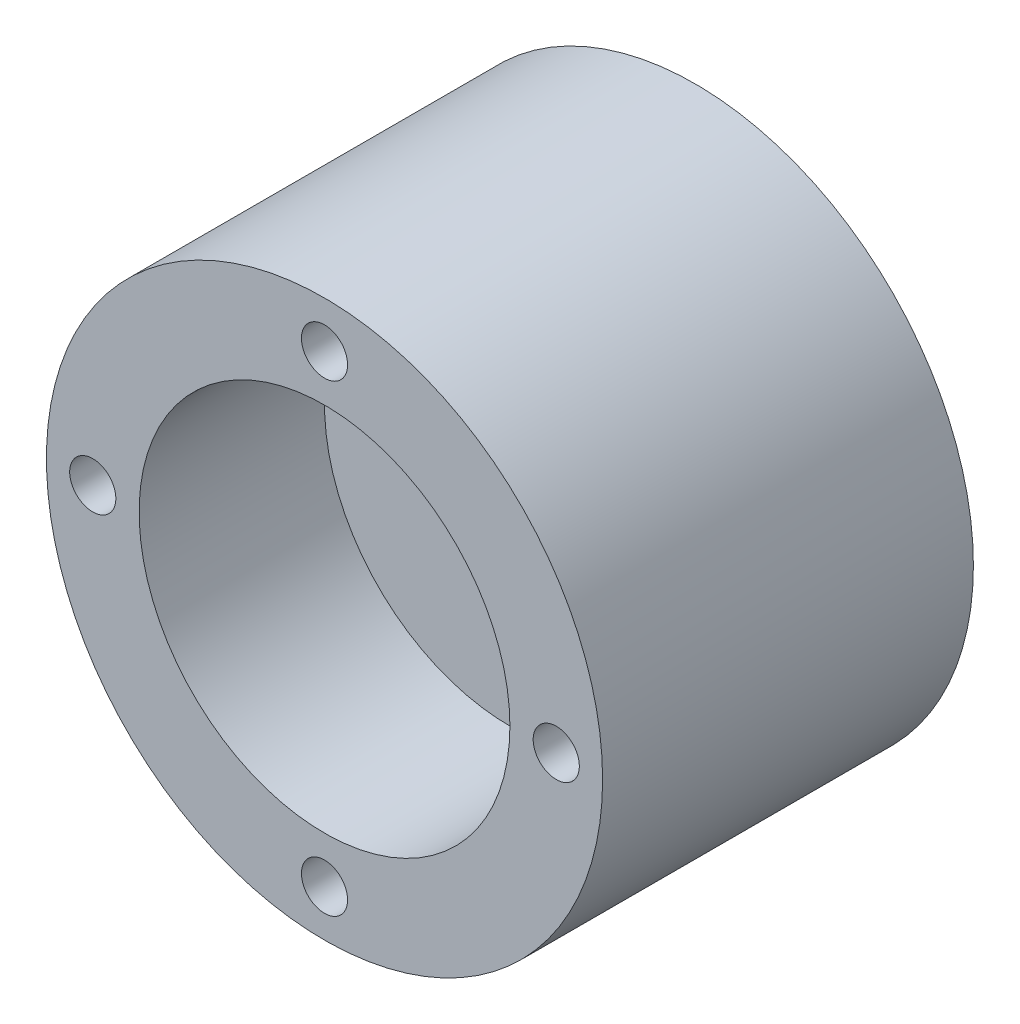
SolidWorks part; units mm, degrees
ref_plane "Front Plane" through (0, 0, 0) normal (0, 0, 1) x (1, 0, 0)
ref_plane "Top Plane" through (0, 0, 0) normal (0, 1, 0) x (1, 0, 0)
ref_plane "Right Plane" through (0, 0, 0) normal (1, 0, 0) x (0, 0, -1)
sketch "Sketch1" plane through (0, 0, 0) normal (0, 0, 1) x (1, 0, 0)
  circle A0 centre (0, 0) radius 38.1
  dimension "D1" = 76.2
extrude "Boss-Extrude1" add sketch "Sketch1" along normal blind 50.8
sketch "Sketch2" plane through (0, 0, 50.8) normal (0, 0, 1) x (1, 0, 0)
  line L0 (-31.75, 0) -> (31.75, 0) construction
  line L1 (0, 31.75) -> (0, -31.75) construction
  circle A0 centre (0, 0) radius 7.9375
  circle A1 centre (0, 31.75) radius 3.1623
  circle A2 centre (0, -31.75) radius 3.1623
  circle A3 centre (31.75, 0) radius 3.1623
  circle A4 centre (-31.75, 0) radius 3.1623
  dimension "D1" = 15.875
  dimension "D2" = 6.3246
  dimension "D3" = 6.3246
  dimension "D4" = 6.3246
  dimension "D5" = 6.3246
  dimension "D6" = 31.75
  dimension "D7" = 31.75
  dimension "D8" = 31.75
  dimension "D9" = 31.75
  dimension "D10" = 90
  dimension "D11" = 90
extrude "Cut-Extrude1" cut sketch "Sketch2" against normal blind 50.8
sketch "Sketch3" plane through (0, 0, 50.8) normal (0, 0, 1) x (1, 0, 0)
  circle A0 centre (0, 0) radius 25.4
  dimension "D1" = 50.8
extrude "Cut-Extrude2" cut sketch "Sketch3" against normal blind 25.4
